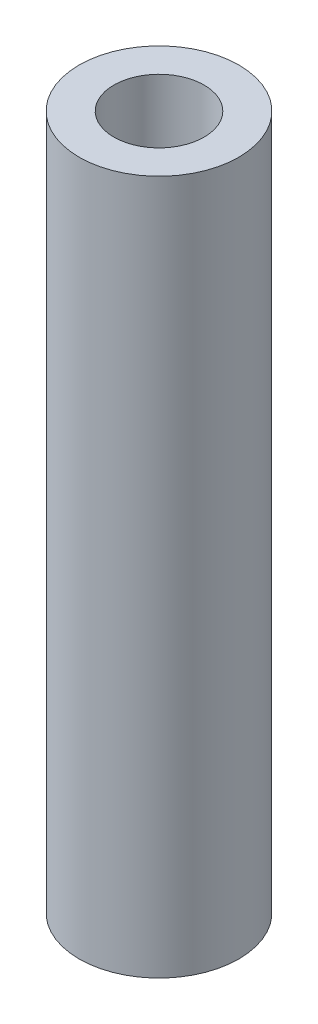
SolidWorks part; units mm, degrees
ref_plane "Front Plane" through (0, 0, 0) normal (0, 0, 1) x (1, 0, 0)
ref_plane "Top Plane" through (0, 0, 0) normal (0, 1, 0) x (1, 0, 0)
ref_plane "Right Plane" through (0, 0, 0) normal (1, 0, 0) x (0, 0, -1)
sketch "Sketch1" plane through (0, 0, 0) normal (0, 1, 0) x (1, 0, 0)
  circle A0 centre (0, 0) radius 1.651
  circle A1 centre (0, 0) radius 2.921
  dimension "D1" = 3.302
  dimension "D2" = 1.27
extrude "Boss-Extrude1" add sketch "Sketch1" along normal blind 25.4
